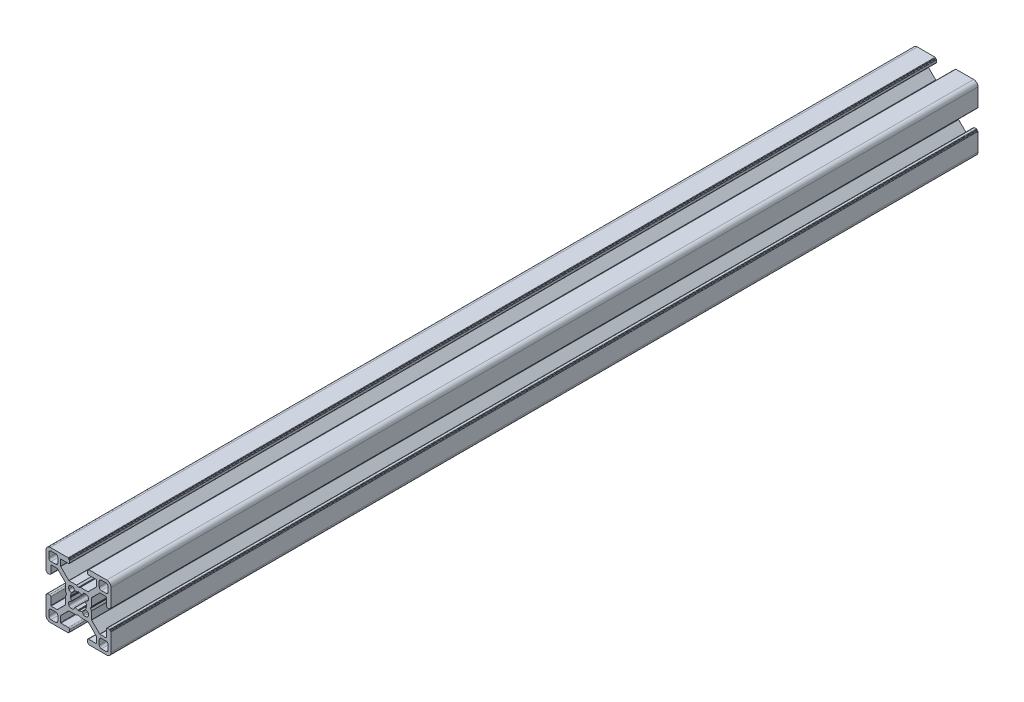
SolidWorks part; units mm, degrees
material "6063-T6"
ref_plane "Front Plane" through (0, 0, 0) normal (0, 0, 1) x (1, 0, 0)
ref_plane "Top Plane" through (0, 0, 0) normal (0, 1, 0) x (1, 0, 0)
ref_plane "Right Plane" through (0, 0, 0) normal (1, 0, 0) x (0, 0, -1)
sketch "Sketch1" plane through (0, 0, 0) normal (0, 0, 1) x (1, 0, 0)
  line L0 (15, -4.7974) -> (15, -12.9934)
  line L1 (12.9934, -15) -> (4.7974, -15)
  line L2 (0, 401018.6297) -> (0, 200019.3665) construction
  line L3 (0, 0) -> (12.9934, -12.9934) construction
  line L4 (-5.53, 0) -> (5.53, 0) construction
  line L5 (4.5974, -14.8) -> (4.5974, -14.7018)
  line L6 (4.3974, -14.5018) -> (4.2513, -14.5018)
  line L7 (4.0513, -14.3018) -> (4.0513, -13.4096)
  line L8 (4.6609, -12.8) -> (8.055, -12.8)
  line L9 (8.255, -12.6) -> (8.255, -9.8935)
  line L10 (8.1964, -9.7521) -> (4.51, -6.0657)
  line L11 (10.555, -9.555) -> (12.7, -9.555)
  line L12 (9.555, -10.555) -> (9.555, -12.7)
  line L13 (10.555, -13.7) -> (12.7, -13.7)
  line L14 (13.4096, -4.0513) -> (14.3018, -4.0513)
  line L15 (14.5018, -4.2513) -> (14.5018, -4.3974)
  line L16 (14.7018, -4.5974) -> (14.8, -4.5974)
  line L17 (12.9934, -12.9934) -> (14.4123, -14.4123) construction
  line L18 (13.7, -10.555) -> (13.7, -12.7)
  line L19 (9.555, -9.555) -> (13.7, -13.7) construction
  line L20 (9.555, -13.7) -> (13.7, -9.555) construction
  line L21 (4.3686, -6.0071) -> (0.9335, -6.0071)
  line L22 (12.8, -4.6609) -> (12.8, -8.055)
  line L23 (12.6, -8.255) -> (9.8935, -8.255)
  line L24 (9.7521, -8.1964) -> (6.0657, -4.51)
  line L25 (-2.6497, 4.5071) -> (-3.5071, 4.5071)
  line L26 (-1.773, 3.4059) -> (-2.2061, 4.238)
  line L27 (6.0071, -4.3686) -> (6.0071, -0.9335)
  line L28 (0.8335, -5.9803) -> (0.1, -5.5568)
  line L29 (-5.9803, 0.8335) -> (-5.5568, 0.1)
  line L30 (0.1, -5.5568) -> (0, -5.4991) construction
  line L31 (-5.9803, -0.8335) -> (-5.5568, -0.1)
  line L32 (5.9803, -0.8335) -> (5.5568, -0.1)
  line L33 (-0.1, -5.5568) -> (0, -5.4991) construction
  line L34 (-9.555, -13.7) -> (-13.7, -9.555) construction
  line L35 (-9.555, -9.555) -> (-13.7, -13.7) construction
  line L36 (-12.9934, -12.9934) -> (-14.4123, -14.4123) construction
  line L37 (0, 0) -> (-12.9934, -12.9934) construction
  line L38 (5.9803, 0.8335) -> (5.5568, 0.1)
  line L39 (-0.8335, -5.9803) -> (-0.1, -5.5568)
  line L40 (-6.0071, -4.3686) -> (-6.0071, -0.9335)
  line L41 (-3.4059, -1.773) -> (-4.238, -2.2061)
  line L42 (-1.773, -3.4059) -> (-2.2061, -4.238)
  line L43 (-9.7521, -8.1964) -> (-6.0657, -4.51)
  line L44 (-12.6, -8.255) -> (-9.8935, -8.255)
  line L45 (-12.8, -4.6609) -> (-12.8, -8.055)
  line L46 (-4.3686, -6.0071) -> (-0.9335, -6.0071)
  line L47 (-13.7, -10.555) -> (-13.7, -12.7)
  line L48 (-14.7018, -4.5974) -> (-14.8, -4.5974)
  line L49 (-14.5018, -4.2513) -> (-14.5018, -4.3974)
  line L50 (-13.4096, -4.0513) -> (-14.3018, -4.0513)
  line L51 (-10.555, -13.7) -> (-12.7, -13.7)
  line L52 (-9.555, -10.555) -> (-9.555, -12.7)
  line L53 (-10.555, -9.555) -> (-12.7, -9.555)
  line L54 (-8.1964, -9.7521) -> (-4.51, -6.0657)
  line L55 (-8.255, -12.6) -> (-8.255, -9.8935)
  line L56 (-4.6609, -12.8) -> (-8.055, -12.8)
  line L57 (-4.0513, -14.3018) -> (-4.0513, -13.4096)
  line L58 (0, -401018.6297) -> (0, -200019.3665) construction
  line L59 (-4.3974, -14.5018) -> (-4.2513, -14.5018)
  line L60 (-4.5974, -14.8) -> (-4.5974, -14.7018)
  line L61 (-12.9934, -15) -> (-4.7974, -15)
  line L62 (-15, -4.7974) -> (-15, -12.9934)
  line L63 (0, 401018.6297) -> (0, 200019.3665) construction
  line L64 (0, -401018.6297) -> (0, -200019.3665) construction
  line L65 (0, 401018.6297) -> (0, 200019.3665) construction
  line L66 (0, -401018.6297) -> (0, -200019.3665) construction
  line L67 (0, 401018.6297) -> (0, 200019.3665) construction
  line L68 (0, -401018.6297) -> (0, -200019.3665) construction
  line L69 (0, 401018.6297) -> (0, 200019.3665) construction
  line L70 (0, 0) -> (-12.9934, 12.9934) construction
  line L71 (-12.9934, 12.9934) -> (-14.4123, 14.4123) construction
  line L72 (-9.555, 9.555) -> (-13.7, 13.7) construction
  line L73 (-9.555, 13.7) -> (-13.7, 9.555) construction
  line L74 (-0.1, 5.5568) -> (0, 5.4991) construction
  line L75 (0, -5.53) -> (0, 5.53) construction
  line L76 (0, -5.53) -> (0, 5.53) construction
  line L77 (0.1, 5.5568) -> (0, 5.4991) construction
  line L78 (9.555, 13.7) -> (13.7, 9.555) construction
  line L79 (9.555, 9.555) -> (13.7, 13.7) construction
  line L80 (12.9934, 12.9934) -> (14.4123, 14.4123) construction
  line L81 (0, 0) -> (12.9934, 12.9934) construction
  line L82 (-15, 4.7974) -> (-15, 12.9934)
  line L83 (-12.9934, 15) -> (-4.7974, 15)
  line L84 (-4.5974, 14.8) -> (-4.5974, 14.7018)
  line L85 (-4.3974, 14.5018) -> (-4.2513, 14.5018)
  line L86 (-4.0513, 14.3018) -> (-4.0513, 13.4096)
  line L87 (-4.6609, 12.8) -> (-8.055, 12.8)
  line L88 (-8.255, 12.6) -> (-8.255, 9.8935)
  line L89 (-8.1964, 9.7521) -> (-4.51, 6.0657)
  line L90 (-10.555, 9.555) -> (-12.7, 9.555)
  line L91 (-9.555, 10.555) -> (-9.555, 12.7)
  line L92 (-10.555, 13.7) -> (-12.7, 13.7)
  line L93 (-13.4096, 4.0513) -> (-14.3018, 4.0513)
  line L94 (-14.5018, 4.2513) -> (-14.5018, 4.3974)
  line L95 (-14.7018, 4.5974) -> (-14.8, 4.5974)
  line L96 (-13.7, 10.555) -> (-13.7, 12.7)
  line L97 (-4.3686, 6.0071) -> (-0.9335, 6.0071)
  line L98 (-12.8, 4.6609) -> (-12.8, 8.055)
  line L99 (-12.6, 8.255) -> (-9.8935, 8.255)
  line L100 (-9.7521, 8.1964) -> (-6.0657, 4.51)
  line L101 (-4.5071, 2.6497) -> (-4.5071, 3.5071)
  line L102 (-3.4059, 1.773) -> (-4.238, 2.2061)
  line L103 (-6.0071, 4.3686) -> (-6.0071, 0.9335)
  line L104 (-0.8335, 5.9803) -> (-0.1, 5.5568)
  line L105 (0, -5.53) -> (0, 5.53) construction
  line L106 (0, -5.53) -> (0, 5.53) construction
  line L107 (0.8335, 5.9803) -> (0.1, 5.5568)
  line L108 (6.0071, 4.3686) -> (6.0071, 0.9335)
  line L109 (1.773, -3.4059) -> (2.2061, -4.238)
  line L110 (2.6497, -4.5071) -> (3.5071, -4.5071)
  line L111 (9.7521, 8.1964) -> (6.0657, 4.51)
  line L112 (12.6, 8.255) -> (9.8935, 8.255)
  line L113 (12.8, 4.6609) -> (12.8, 8.055)
  line L114 (4.3686, 6.0071) -> (0.9335, 6.0071)
  line L115 (13.7, 10.555) -> (13.7, 12.7)
  line L116 (14.7018, 4.5974) -> (14.8, 4.5974)
  line L117 (14.5018, 4.2513) -> (14.5018, 4.3974)
  line L118 (13.4096, 4.0513) -> (14.3018, 4.0513)
  line L119 (10.555, 13.7) -> (12.7, 13.7)
  line L120 (9.555, 10.555) -> (9.555, 12.7)
  line L121 (10.555, 9.555) -> (12.7, 9.555)
  line L122 (8.1964, 9.7521) -> (4.51, 6.0657)
  line L123 (8.255, 12.6) -> (8.255, 9.8935)
  line L124 (4.6609, 12.8) -> (8.055, 12.8)
  line L125 (4.0513, 14.3018) -> (4.0513, 13.4096)
  line L126 (4.3974, 14.5018) -> (4.2513, 14.5018)
  line L127 (4.5974, 14.8) -> (4.5974, 14.7018)
  line L128 (12.9934, 15) -> (4.7974, 15)
  line L129 (15, 4.7974) -> (15, 12.9934)
  line L130 (-2.6497, -4.5071) -> (-3.5071, -4.5071)
  line L131 (-4.5071, -2.6497) -> (-4.5071, -3.5071)
  line L132 (4.5071, -2.6497) -> (4.5071, -3.5071)
  line L133 (3.4059, -1.773) -> (4.238, -2.2061)
  line L134 (3.4059, 1.773) -> (4.238, 2.2061)
  line L135 (4.5071, 2.6497) -> (4.5071, 3.5071)
  line L136 (2.6497, 4.5071) -> (3.5071, 4.5071)
  line L137 (1.773, 3.4059) -> (2.2061, 4.238)
  line L138 (-0.1, -3.7585) -> (-0.2836, -3.6525)
  line L139 (0.1, -3.7585) -> (0.2836, -3.6525)
  line L140 (-3.7585, 0.1) -> (-3.6525, 0.2836)
  line L141 (-3.7585, -0.1) -> (-3.6525, -0.2836)
  line L142 (3.7585, -0.1) -> (3.6525, -0.2836)
  line L143 (3.7585, 0.1) -> (3.6525, 0.2836)
  line L144 (0.1, 3.7585) -> (0.2836, 3.6525)
  line L145 (-0.1, 3.7585) -> (-0.2836, 3.6525)
  line L146 (0, 5.53) -> (0, -5.53) construction
  line L147 (0, 5.53) -> (0, -5.53) construction
  line L148 (0, 5.53) -> (0, -5.53) construction
  line L149 (0, 5.53) -> (0, -5.53) construction
  line L150 (0, 5.53) -> (0, -5.53) construction
  arc A0 (15, -12.9934) -> (12.9934, -15) centre (12.9934, -12.9934) cw
  arc A1 (9.555, -12.7) -> (10.555, -13.7) centre (10.555, -12.7) ccw
  arc A2 (10.555, -9.555) -> (9.555, -10.555) centre (10.555, -10.555) ccw
  arc A3 (13.7, -10.555) -> (12.7, -9.555) centre (12.7, -10.555) ccw
  arc A4 (13.7, -12.7) -> (12.7, -13.7) centre (12.7, -12.7) cw
  arc A5 (4.51, -6.0657) -> (4.3686, -6.0071) centre (4.3686, -6.2071) ccw
  arc A6 (8.255, -9.8935) -> (8.1964, -9.7521) centre (8.055, -9.8935) ccw
  arc A7 (6.0657, -4.51) -> (6.0071, -4.3686) centre (6.2071, -4.3686) cw
  arc A8 (9.8935, -8.255) -> (9.7521, -8.1964) centre (9.8935, -8.055) cw
  arc A9 (12.8, -8.055) -> (12.6, -8.255) centre (12.6, -8.055) cw
  arc A10 (-1.5126, -3.3162) -> (-0.3636, -3.6267) centre (0, 0) ccw
  arc A11 (3.3162, -1.5126) -> (3.6267, -0.3636) centre (0, 0) ccw
  arc A12 (13.4096, -4.0513) -> (12.8, -4.6609) centre (13.4096, -4.6609) ccw
  arc A13 (-2.2061, 4.238) -> (-2.6497, 4.5071) centre (-2.6497, 4.0071) ccw
  arc A14 (-1.5126, 3.3162) -> (-1.773, 3.4059) centre (-1.5956, 3.4982) cw
  arc A15 (-8.255, -12.6) -> (-8.055, -12.8) centre (-8.055, -12.6) ccw
  arc A16 (-3.5071, 4.5071) -> (-4.5071, 3.5071) centre (-3.5071, 3.5071) ccw
  arc A17 (-6.0071, -0.9335) -> (-5.9803, -0.8335) centre (-5.8071, -0.9335) cw
  arc A18 (-4.238, 2.2061) -> (-4.5071, 2.6497) centre (-4.0071, 2.6497) cw
  arc A19 (-3.3162, 1.5126) -> (-3.4059, 1.773) centre (-3.4982, 1.5956) ccw
  arc A20 (-0.8335, -5.9803) -> (-0.9335, -6.0071) centre (-0.9335, -5.8071) cw
  arc A21 (-5.5568, 0.1) -> (-5.5568, -0.1) centre (-5.73, 0) cw
  arc A22 (-14.8, -4.5974) -> (-15, -4.7974) centre (-14.8, -4.7974) ccw
  arc A23 (-4.5974, -14.8) -> (-4.7974, -15) centre (-4.7974, -14.8) cw
  arc A24 (-14.5018, -4.3974) -> (-14.7018, -4.5974) centre (-14.7018, -4.3974) cw
  arc A25 (-4.3974, -14.5018) -> (-4.5974, -14.7018) centre (-4.3974, -14.7018) ccw
  arc A26 (4.6609, -12.8) -> (4.0513, -13.4096) centre (4.6609, -13.4096) ccw
  arc A27 (-14.5018, -4.2513) -> (-14.3018, -4.0513) centre (-14.3018, -4.2513) cw
  arc A28 (4.0513, -14.3018) -> (4.2513, -14.5018) centre (4.2513, -14.3018) ccw
  arc A29 (14.5018, -4.2513) -> (14.3018, -4.0513) centre (14.3018, -4.2513) ccw
  arc A30 (4.3974, -14.5018) -> (4.5974, -14.7018) centre (4.3974, -14.7018) cw
  arc A31 (14.5018, -4.3974) -> (14.7018, -4.5974) centre (14.7018, -4.3974) ccw
  arc A32 (4.5974, -14.8) -> (4.7974, -15) centre (4.7974, -14.8) ccw
  arc A33 (14.8, -4.5974) -> (15, -4.7974) centre (14.8, -4.7974) cw
  arc A34 (0.1, -5.5568) -> (-0.1, -5.5568) centre (0, -5.73) ccw
  arc A35 (-4.0513, -14.3018) -> (-4.2513, -14.5018) centre (-4.2513, -14.3018) cw
  arc A36 (5.5568, 0.1) -> (5.5568, -0.1) centre (5.73, 0) ccw
  arc A37 (0.8335, -5.9803) -> (0.9335, -6.0071) centre (0.9335, -5.8071) ccw
  arc A38 (6.0071, -0.9335) -> (5.9803, -0.8335) centre (5.8071, -0.9335) ccw
  arc A39 (-4.6609, -12.8) -> (-4.0513, -13.4096) centre (-4.6609, -13.4096) cw
  arc A40 (-3.5071, -4.5071) -> (-4.5071, -3.5071) centre (-3.5071, -3.5071) cw
  arc A41 (-4.238, -2.2061) -> (-4.5071, -2.6497) centre (-4.0071, -2.6497) ccw
  arc A42 (-2.2061, -4.238) -> (-2.6497, -4.5071) centre (-2.6497, -4.0071) cw
  arc A43 (-3.3162, -1.5126) -> (-3.4059, -1.773) centre (-3.4982, -1.5956) cw
  arc A44 (-1.5126, -3.3162) -> (-1.773, -3.4059) centre (-1.5956, -3.4982) ccw
  arc A45 (-13.4096, -4.0513) -> (-12.8, -4.6609) centre (-13.4096, -4.6609) cw
  arc A46 (-3.3162, -1.5126) -> (-3.6267, -0.3636) centre (0, 0) cw
  arc A47 (-12.8, -8.055) -> (-12.6, -8.255) centre (-12.6, -8.055) ccw
  arc A48 (-9.8935, -8.255) -> (-9.7521, -8.1964) centre (-9.8935, -8.055) ccw
  arc A49 (-6.0657, -4.51) -> (-6.0071, -4.3686) centre (-6.2071, -4.3686) ccw
  arc A50 (-8.255, -9.8935) -> (-8.1964, -9.7521) centre (-8.055, -9.8935) cw
  arc A51 (-4.51, -6.0657) -> (-4.3686, -6.0071) centre (-4.3686, -6.2071) cw
  arc A52 (-13.7, -12.7) -> (-12.7, -13.7) centre (-12.7, -12.7) ccw
  arc A53 (-13.7, -10.555) -> (-12.7, -9.555) centre (-12.7, -10.555) cw
  arc A54 (-10.555, -9.555) -> (-9.555, -10.555) centre (-10.555, -10.555) cw
  arc A55 (-9.555, -12.7) -> (-10.555, -13.7) centre (-10.555, -12.7) cw
  arc A56 (-15, -12.9934) -> (-12.9934, -15) centre (-12.9934, -12.9934) ccw
  arc A57 (8.255, 12.6) -> (8.055, 12.8) centre (8.055, 12.6) ccw
  arc A58 (-15, 12.9934) -> (-12.9934, 15) centre (-12.9934, 12.9934) cw
  arc A59 (-9.555, 12.7) -> (-10.555, 13.7) centre (-10.555, 12.7) ccw
  arc A60 (-10.555, 9.555) -> (-9.555, 10.555) centre (-10.555, 10.555) ccw
  arc A61 (-13.7, 10.555) -> (-12.7, 9.555) centre (-12.7, 10.555) ccw
  arc A62 (-13.7, 12.7) -> (-12.7, 13.7) centre (-12.7, 12.7) cw
  arc A63 (-4.51, 6.0657) -> (-4.3686, 6.0071) centre (-4.3686, 6.2071) ccw
  arc A64 (-8.255, 9.8935) -> (-8.1964, 9.7521) centre (-8.055, 9.8935) ccw
  arc A65 (-6.0657, 4.51) -> (-6.0071, 4.3686) centre (-6.2071, 4.3686) cw
  arc A66 (-9.8935, 8.255) -> (-9.7521, 8.1964) centre (-9.8935, 8.055) cw
  arc A67 (-12.8, 8.055) -> (-12.6, 8.255) centre (-12.6, 8.055) cw
  arc A68 (-13.4096, 4.0513) -> (-12.8, 4.6609) centre (-13.4096, 4.6609) ccw
  arc A69 (1.5126, -3.3162) -> (1.773, -3.4059) centre (1.5956, -3.4982) cw
  arc A70 (2.2061, -4.238) -> (2.6497, -4.5071) centre (2.6497, -4.0071) ccw
  arc A71 (3.5071, -4.5071) -> (4.5071, -3.5071) centre (3.5071, -3.5071) ccw
  arc A72 (4.238, -2.2061) -> (4.5071, -2.6497) centre (4.0071, -2.6497) cw
  arc A73 (3.3162, -1.5126) -> (3.4059, -1.773) centre (3.4982, -1.5956) ccw
  arc A74 (-4.6609, 12.8) -> (-4.0513, 13.4096) centre (-4.6609, 13.4096) ccw
  arc A75 (6.0071, 0.9335) -> (5.9803, 0.8335) centre (5.8071, 0.9335) cw
  arc A76 (0.8335, 5.9803) -> (0.9335, 6.0071) centre (0.9335, 5.8071) cw
  arc A77 (-4.0513, 14.3018) -> (-4.2513, 14.5018) centre (-4.2513, 14.3018) ccw
  arc A78 (0.1, 5.5568) -> (-0.1, 5.5568) centre (0, 5.73) cw
  arc A79 (14.8, 4.5974) -> (15, 4.7974) centre (14.8, 4.7974) ccw
  arc A80 (4.5974, 14.8) -> (4.7974, 15) centre (4.7974, 14.8) cw
  arc A81 (14.5018, 4.3974) -> (14.7018, 4.5974) centre (14.7018, 4.3974) cw
  arc A82 (4.3974, 14.5018) -> (4.5974, 14.7018) centre (4.3974, 14.7018) ccw
  arc A83 (14.5018, 4.2513) -> (14.3018, 4.0513) centre (14.3018, 4.2513) cw
  arc A84 (4.0513, 14.3018) -> (4.2513, 14.5018) centre (4.2513, 14.3018) cw
  arc A85 (-14.5018, 4.2513) -> (-14.3018, 4.0513) centre (-14.3018, 4.2513) ccw
  arc A86 (4.6609, 12.8) -> (4.0513, 13.4096) centre (4.6609, 13.4096) cw
  arc A87 (-4.3974, 14.5018) -> (-4.5974, 14.7018) centre (-4.3974, 14.7018) cw
  arc A88 (-14.5018, 4.3974) -> (-14.7018, 4.5974) centre (-14.7018, 4.3974) ccw
  arc A89 (-4.5974, 14.8) -> (-4.7974, 15) centre (-4.7974, 14.8) ccw
  arc A90 (-14.8, 4.5974) -> (-15, 4.7974) centre (-14.8, 4.7974) cw
  arc A91 (-0.8335, 5.9803) -> (-0.9335, 6.0071) centre (-0.9335, 5.8071) ccw
  arc A92 (3.3162, 1.5126) -> (3.4059, 1.773) centre (3.4982, 1.5956) cw
  arc A93 (4.238, 2.2061) -> (4.5071, 2.6497) centre (4.0071, 2.6497) ccw
  arc A94 (-6.0071, 0.9335) -> (-5.9803, 0.8335) centre (-5.8071, 0.9335) ccw
  arc A95 (3.5071, 4.5071) -> (4.5071, 3.5071) centre (3.5071, 3.5071) cw
  arc A96 (-8.255, 12.6) -> (-8.055, 12.8) centre (-8.055, 12.6) cw
  arc A97 (2.2061, 4.238) -> (2.6497, 4.5071) centre (2.6497, 4.0071) cw
  arc A98 (1.5126, 3.3162) -> (1.773, 3.4059) centre (1.5956, 3.4982) ccw
  arc A99 (13.4096, 4.0513) -> (12.8, 4.6609) centre (13.4096, 4.6609) cw
  arc A100 (-1.5126, 3.3162) -> (-0.3636, 3.6267) centre (0, 0) cw
  arc A101 (12.8, 8.055) -> (12.6, 8.255) centre (12.6, 8.055) ccw
  arc A102 (9.8935, 8.255) -> (9.7521, 8.1964) centre (9.8935, 8.055) ccw
  arc A103 (6.0657, 4.51) -> (6.0071, 4.3686) centre (6.2071, 4.3686) ccw
  arc A104 (8.255, 9.8935) -> (8.1964, 9.7521) centre (8.055, 9.8935) cw
  arc A105 (4.51, 6.0657) -> (4.3686, 6.0071) centre (4.3686, 6.2071) cw
  arc A106 (13.7, 12.7) -> (12.7, 13.7) centre (12.7, 12.7) ccw
  arc A107 (13.7, 10.555) -> (12.7, 9.555) centre (12.7, 10.555) cw
  arc A108 (10.555, 9.555) -> (9.555, 10.555) centre (10.555, 10.555) cw
  arc A109 (9.555, 12.7) -> (10.555, 13.7) centre (10.555, 12.7) cw
  arc A110 (15, 12.9934) -> (12.9934, 15) centre (12.9934, 12.9934) ccw
  arc A111 (0.3636, -3.6267) -> (1.5126, -3.3162) centre (0, 0) ccw
  arc A112 (0.3636, -3.6267) -> (0.2836, -3.6525) centre (0.3836, -3.8257) ccw
  arc A113 (-0.1, -3.7585) -> (0.1, -3.7585) centre (0, -3.5853) ccw
  arc A114 (-0.2836, -3.6525) -> (-0.3636, -3.6267) centre (-0.3836, -3.8257) ccw
  arc A115 (-3.6267, 0.3636) -> (-3.6525, 0.2836) centre (-3.8257, 0.3836) cw
  arc A116 (-3.7585, -0.1) -> (-3.7585, 0.1) centre (-3.5853, 0) cw
  arc A117 (-3.6525, -0.2836) -> (-3.6267, -0.3636) centre (-3.8257, -0.3836) cw
  arc A118 (-3.6267, 0.3636) -> (-3.3162, 1.5126) centre (0, 0) cw
  arc A119 (3.6267, -0.3636) -> (3.6525, -0.2836) centre (3.8257, -0.3836) cw
  arc A120 (3.7585, 0.1) -> (3.7585, -0.1) centre (3.5853, 0) cw
  arc A121 (3.6525, 0.2836) -> (3.6267, 0.3636) centre (3.8257, 0.3836) cw
  arc A122 (0.2836, 3.6525) -> (0.3636, 3.6267) centre (0.3836, 3.8257) ccw
  arc A123 (0.1, 3.7585) -> (-0.1, 3.7585) centre (0, 3.5853) ccw
  arc A124 (-0.3636, 3.6267) -> (-0.2836, 3.6525) centre (-0.3836, 3.8257) ccw
  arc A125 (3.6267, 0.3636) -> (3.3162, 1.5126) centre (0, 0) ccw
  arc A126 (0.3636, 3.6267) -> (1.5126, 3.3162) centre (0, 0) cw
  arc A144 (8.255, -12.6) -> (8.055, -12.8) centre (8.055, -12.6) cw
  point P11 (11.6275, -11.6275)
  point P143 (-4.5071, -4.5071)
  point P147 (-4.5071, -2.3462)
  point P182 (-8.255, -12.8)
  point P186 (-11.6275, -11.6275)
  point P333 (0.3213, -3.6307)
  point P365 (8.255, 12.8)
  point P366 (-11.6275, 11.6275)
  point P370 (-8.255, 12.8)
  point P374 (11.6275, 11.6275)
  point P376 (-2.3462, -4.5071)
  point P379 (-3.2331, -1.683)
  point P382 (-1.683, -3.2331)
  point P400 (0, -3.8162)
  point P404 (8.255, -12.8)
  point P406 (-0.3213, -3.6307)
  dimension "D2" = 30
  dimension "D3" = 2.0066
  dimension "D8" = 12.0142
  dimension "D9" = 0.6096
  dimension "D11" = 1
  dimension "D12" = 1.3
  dimension "D6" = 1.3
  dimension "D14" = 10.9982
  dimension "D18" = 27.5
  dimension "D19" = 1.5
  dimension "D20" = 2.2
  dimension "D25" = 0.5
  dimension "D27" = 0.2
  dimension "D28" = 0.2
  dimension "D30" = 0.2
  dimension "D22" = 7.2898
  dimension "D38" = 1
  dimension "D39" = 0.5
  dimension "D40" = 0.2
  dimension "D4" = 8.1026
  dimension "D5" = 1.7018
  dimension "D7" = 16.51
  dimension "D10" = 2.2
  dimension "D17" = 9.1948
  dimension "D21" = 120
  dimension "D31" = 60
extrude "Boss-Extrude1" add sketch "Sketch1" along normal mid plane 400
